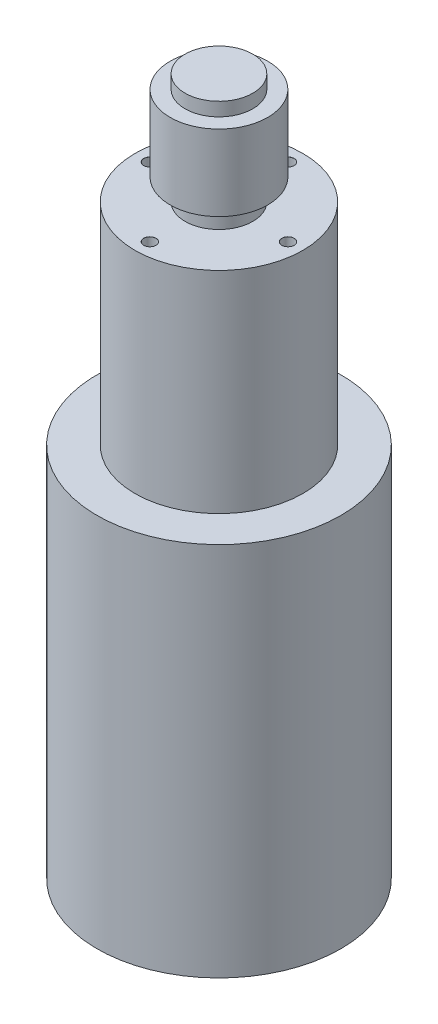
SolidWorks part; units mm, degrees
material "Acciaio al carbonio semplice"
ref_plane "Piano frontale" through (0, 0, 0) normal (0, 0, 1) x (1, 0, 0)
ref_plane "Piano superiore" through (0, 0, 0) normal (0, 1, 0) x (1, 0, 0)
ref_plane "Piano destro" through (0, 0, 0) normal (1, 0, 0) x (0, 0, -1)
sketch "Schizzo2" plane through (0, 0, 0) normal (0, 0, 1) x (1, 0, 0)
  line L0 (0, -1182.3942) -> (0, 57937.316) construction
  line L1 (0, 257.3) -> (12.5, 257.3)
  line L2 (12.5, 257.3) -> (12.5, 252.3)
  line L3 (12.5, 252.3) -> (18, 252.3)
  line L4 (18, 252.3) -> (18, 224.3)
  line L5 (18, 224.3) -> (12.5, 224.3)
  line L6 (12.5, 224.3) -> (12.5, 216.3)
  line L7 (12.5, 216.3) -> (31, 216.3)
  line L8 (31, 216.3) -> (31, 138.55)
  line L9 (31, 138.55) -> (45, 138.55)
  line L10 (45, 138.55) -> (45, 0)
  line L11 (45, 0) -> (0, 0)
  line L12 (0, 257.3) -> (0, 0)
  point P5 (31, 177.425)
  dimension "D1" = 45
  dimension "D2" = 138.55
  dimension "D3" = 31
  dimension "D4" = 8
  dimension "D5" = 77.75
  dimension "D6" = 12.5
  dimension "D7" = 33
  dimension "D8" = 5
  dimension "D9" = 18
revolve "Rivoluzione1" add sketch "Schizzo2" angle 360 about L0
hole_wizard "Foro per Vite M4-1" positions "Schizzo7" profile "Schizzo6" hole size "M4" standard "ISO"
sketch "Schizzo7" plane through (0, 216.3, 0) normal (0, 1, 0) x (1, 0, 0)
  point P0 (0, 25.5)
  point P2 (25.5, 0)
  point P4 (0, -25.5)
  point P6 (-25.5, 0)
  dimension "D1" = 25.5
  dimension "D2" = 25.5
  dimension "D3" = 25.5
  dimension "D4" = 25.5
sketch "Schizzo6" plane through (0, 216.3, -25.5) normal (1, 0, 0) x (0, 0, 1)
  line L0 (0, 0) -> (0, 18.3519)
  line L1 (0, 18.3519) -> (2.25, 17)
  line L2 (2.25, 17) -> (2.25, 0.025)
  line L3 (2.25, 0.025) -> (2.275, 0)
  line L5 (2.275, 0) -> (0, 0)
  line L6 (-2.25, 0.025) -> (-2.275, 0) construction
  line L10 (0, 18.3519) -> (-2.25, 17) construction
  line L11 (0, -6.35) -> (0, 107.95) construction
  dimension "Hole Dia." = 4.5
  dimension "Hole Depth" = 17
  dimension "Near C'Sink Dia." = 4.55
  dimension "Near C'Sink Angle" = 90
  dimension "Drill Angle" = 118
